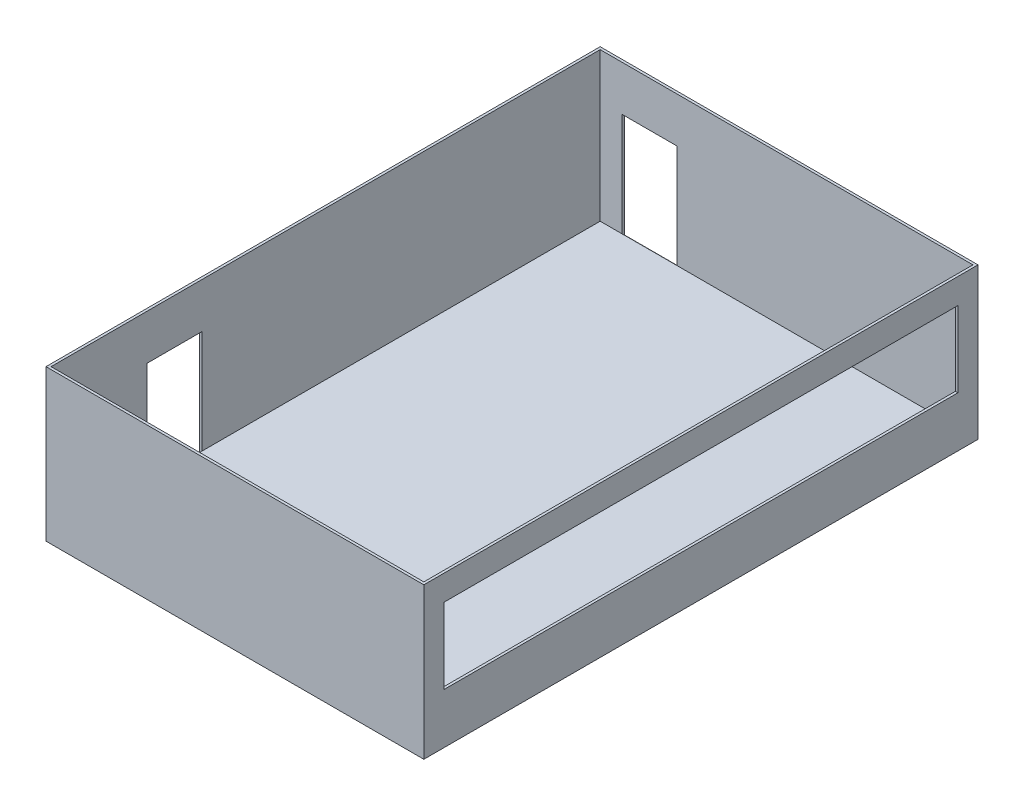
SolidWorks part; units mm, degrees
ref_plane "Front Plane" through (0, 0, 0) normal (0, 0, 1) x (1, 0, 0)
ref_plane "Top Plane" through (0, 0, 0) normal (0, 1, 0) x (1, 0, 0)
ref_plane "Right Plane" through (0, 0, 0) normal (1, 0, 0) x (0, 0, -1)
sketch "Sketch3" plane through (0, 0, 0) normal (0, 1, 0) x (1, 0, 0)
  line L1 (3750, -5500) -> (-3750, -5500)
  line L2 (3750, -5500) -> (3750, 5500)
  line L3 (3750, 5500) -> (-3750, 5500)
  line L4 (-3750, -5500) -> (-3750, 5500)
  line L5 (3750, -5500) -> (-3750, 5500) construction
  line L6 (3750, 5500) -> (-3750, -5500) construction
  point P0 (0, 0)
  dimension "D1" = 7500
  dimension "D2" = 11000
extrude "Boss-Extrude1" add sketch "Sketch3" along normal blind 3000
shell "Shell1" thickness 50
sketch "Sketch4" plane through (3750, 0, 0) normal (1, 0, 0) x (0, 0, -1)
  line L0 (-5100, 2500) -> (5100, 2500)
  line L1 (-5100, 2500) -> (0, 2500)
  line L2 (-5100, 2500) -> (-5100, 1000)
  line L3 (-5100, 1000) -> (0, 1000)
  line L4 (0, 2500) -> (0, 1000)
  line L5 (-5100, 2500) -> (0, 1000) construction
  line L6 (-5100, 1000) -> (0, 2500) construction
  line L7 (0, 2500) -> (5100, 2500)
  line L8 (0, 2500) -> (0, 1000)
  line L9 (0, 1000) -> (5100, 1000)
  line L10 (5100, 2500) -> (5100, 1000)
  line L11 (0, 2500) -> (5100, 1000) construction
  line L12 (0, 1000) -> (5100, 2500) construction
  line L13 (-5500, 3000) -> (5500, 3000) construction
  line L15 (0, 0) -> (0, 3780.8865) construction
  line L16 (-5500, 0) -> (5500, 0) construction
  point P4 (-2550, 1750)
  point P8 (2550, 1750)
  dimension "D1" = 5100
  dimension "D2" = 5100
  dimension "D3" = 1500
  dimension "D4" = 1500
  dimension "D5" = 500
extrude "Cut-Extrude1" cut sketch "Sketch4" against normal up to next contours L4 L0 L2 L3 | L10 L0 L4 L9
sketch "Sketch5" plane through (0, 0, -5500) normal (0, 0, -1) x (-1, 0, 0)
  line L0 (-3750, 0) -> (3750, 0) construction
  line L1 (2170, 2105) -> (3270, 2105)
  line L2 (2170, 2105) -> (2170, 5)
  line L3 (2170, 5) -> (3270, 5)
  line L4 (3270, 2105) -> (3270, 5)
  line L5 (2170, 2105) -> (3270, 5) construction
  line L6 (2170, 5) -> (3270, 2105) construction
  line L7 (3750, 3000) -> (3750, 0) construction
  point P4 (2720, 1055)
  dimension "D1" = 2100
  dimension "D2" = 2105
  dimension "D3" = 1100
  dimension "D4" = 480
extrude "Cut-Extrude2" cut sketch "Sketch5" against normal blind 50
sketch "Sketch6" plane through (-3750, 0, 0) normal (-1, 0, 0) x (0, 0, 1)
  line L0 (-2000, 3000) -> (-2000, 0)
  line L1 (-5500, 3000) -> (5500, 3000) construction
  line L2 (-5500, 0) -> (5500, 0) construction
  line L3 (-5500, 3000) -> (-5500, 0) construction
  line L4 (1500, 3000) -> (1500, 0)
  line L5 (1500, 3000) -> (4500, 3000)
  line L6 (4500, 3000) -> (4500, 0)
  line L7 (2450, 2105) -> (3550, 2105)
  line L8 (2450, 2105) -> (2450, 5)
  line L9 (2450, 5) -> (3550, 5)
  line L10 (3550, 2105) -> (3550, 5)
  line L11 (2450, 2105) -> (3550, 5) construction
  line L12 (2450, 5) -> (3550, 2105) construction
  line L13 (3000, 3000) -> (3000, 5) construction
  line L14 (5500, 3000) -> (5500, 0) construction
  point P16 (3000, 1055)
  point P19 (1500, 3000)
  dimension "D1" = 3500
  dimension "D2" = 3500
  dimension "D3" = 3000
  dimension "D4" = 2100
  dimension "D5" = 2105
  dimension "D6" = 1100
  dimension "D7" = 950
  dimension "D8" = 1000
extrude "Cut-Extrude3" cut sketch "Sketch6" against normal blind 50 contours L10 L7 L8 L9
